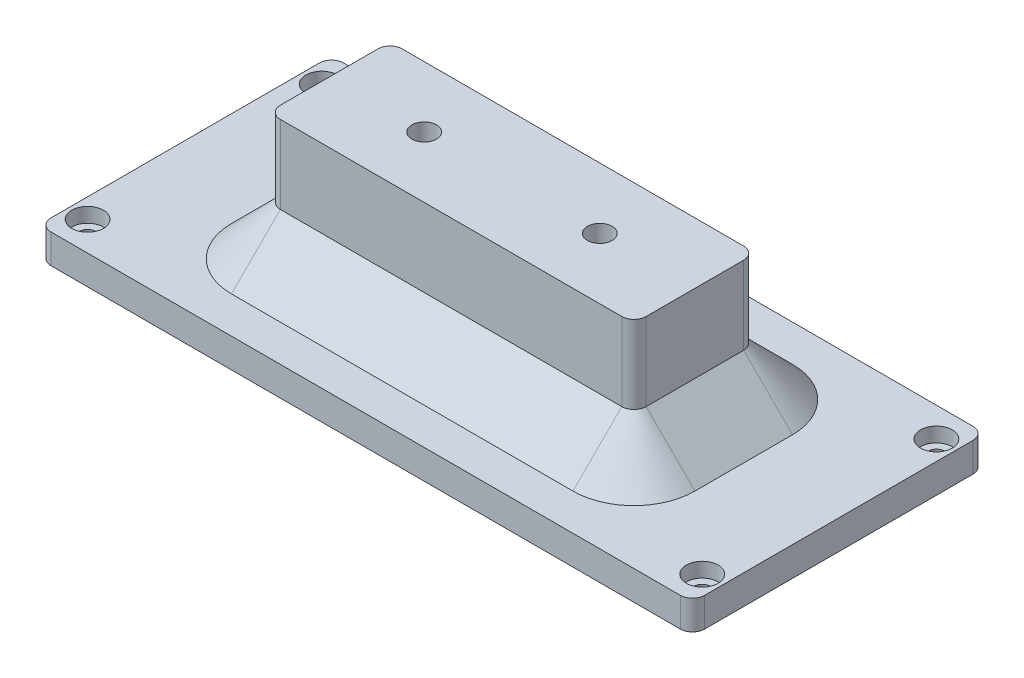
SolidWorks part; units mm, degrees
ref_plane "Front Plane" through (0, 0, 0) normal (0, 0, 1) x (1, 0, 0)
ref_plane "Top Plane" through (0, 0, 0) normal (0, 1, 0) x (1, 0, 0)
ref_plane "Right Plane" through (0, 0, 0) normal (1, 0, 0) x (0, 0, -1)
sketch "Sketch1" plane through (0, 0, 0) normal (0, 1, 0) x (1, 0, 0)
  line L1 (-67, 30) -> (67, 30)
  line L2 (-67, 30) -> (-67, -30)
  line L3 (-67, -30) -> (67, -30)
  line L4 (67, 30) -> (67, -30)
  line L5 (-67, 30) -> (67, -30) construction
  line L6 (-67, -30) -> (67, 30) construction
  point P0 (0, 0)
  dimension "D1" = 60
  dimension "D2" = 134
extrude "Boss-Extrude1" add sketch "Sketch1" along normal blind 6
hole_wizard "CBORE for M3 SHCS1" positions "Sketch2" profile "Sketch3" counterbore size "M3" standard "ANSI Metric"
sketch "Sketch2" plane through (0, 6, 0) normal (0, 1, 0) x (1, 0, 0)
  line L0 (63, 24) -> (63, -24) construction
  line L1 (63, -24) -> (-63, -24) construction
  line L2 (-63, -24) -> (-63, 24) construction
  line L3 (-63, 24) -> (63, 24) construction
  line L6 (-67, -30) -> (67, -30) construction
  line L7 (67, -30) -> (67, 30) construction
  point P0 (-63, 24)
  point P2 (-63, -24)
  point P4 (63, -24)
  point P6 (63, 24)
  point P25 (0, 24)
  point P27 (-63, 0)
  dimension "D1" = 48
  dimension "D2" = 126
sketch "Sketch3" plane through (-63, 6, -24) normal (1, 0, 0) x (0, 0, 1)
  line L0 (0, 0) -> (0, 18.4015)
  line L1 (0, 18.4015) -> (1.7, 17.38)
  line L2 (1.7, 17.38) -> (1.7, 3)
  line L3 (1.7, 3) -> (3.25, 3)
  line L4 (3.25, 3) -> (3.25, 0)
  line L5 (3.25, 0) -> (0, 0)
  line L10 (0, 18.4015) -> (-1.7, 17.38) construction
  line L11 (0, -6.35) -> (0, 107.95) construction
  dimension "Hole Dia." = 3.4
  dimension "Hole Depth" = 17.38
  dimension "C'Bore Dia." = 6.5
  dimension "C'Bore Depth" = 3
  dimension "Drill Angle" = 118
sketch "Sketch4" plane through (0, 6, 0) normal (0, 1, 0) x (1, 0, 0)
  line L1 (-37.5, 12.5) -> (37.5, 12.5)
  line L2 (-37.5, 12.5) -> (-37.5, -12.5)
  line L3 (-37.5, -12.5) -> (37.5, -12.5)
  line L4 (37.5, 12.5) -> (37.5, -12.5)
  line L5 (-37.5, 12.5) -> (37.5, -12.5) construction
  line L6 (-37.5, -12.5) -> (37.5, 12.5) construction
  point P0 (0, 0)
  dimension "D1" = 25
  dimension "D2" = 75
extrude "Boss-Extrude2" add sketch "Sketch4" along normal blind 26
hole_wizard "#8 (0.199) Diameter Hole1" positions "Sketch5" profile "Sketch6" hole size "#8" standard "ANSI Inch" end condition through all
sketch "Sketch5" plane through (0, 32, 0) normal (0, 1, 0) x (1, 0, 0)
  line L0 (18, 0) -> (-18, 0) construction
  point P0 (-18, 0)
  point P2 (18, 0)
  point P9 (0, 0)
  dimension "D1" = 36
sketch "Sketch6" plane through (-18, 32, 0) normal (1, 0, 0) x (0, 0, 1)
  line L0 (0, 0) -> (0, 32)
  line L1 (0, 32) -> (2.5273, 32)
  line L2 (2.5273, 32) -> (2.5273, 0)
  line L5 (2.5273, 0) -> (0, 0)
  line L11 (0, -6.35) -> (0, 107.95) construction
  dimension "Thru Hole Dia." = 5.0546
  dimension "Thru Hole Depth" = 32
fillet "Fillet1" radius 2.5 4 edges at (67, 3, -30) (67, 3, 30) (-67, 3, 30) (-67, 3, -30)
fillet "Fillet2" radius 2.5 4 edges at (37.5, 19, -12.5) (37.5, 19, 12.5) (-37.5, 19, 12.5) (-37.5, 19, -12.5)
chamfer "Chamfer1" distance 10 angle 45 8 edges at (-37.5, 6, 0) (0, 6, -12.5) (37.5, 6, 0) (0, 6, 12.5) (-36.7678, 6, -11.7678) (36.7678, 6, -11.7678) (-36.7678, 6, 11.7678) (36.7678, 6, 11.7678)
